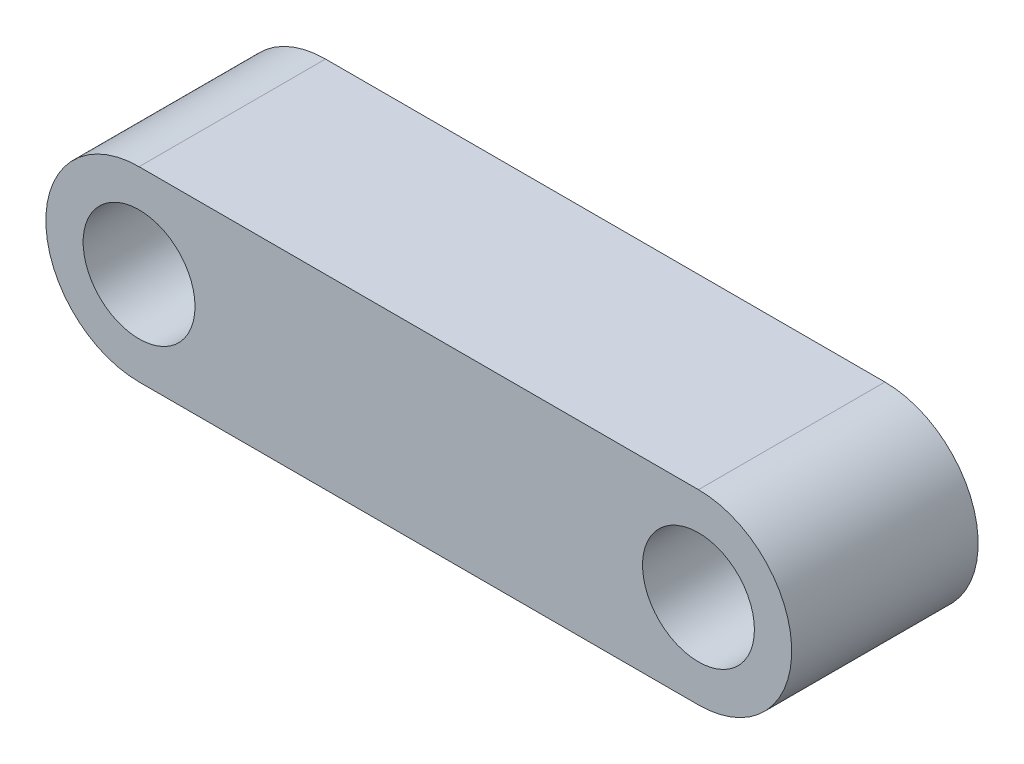
SolidWorks part; units mm, degrees
ref_plane "Front Plane" through (0, 0, 0) normal (0, 0, 1) x (1, 0, 0)
ref_plane "Top Plane" through (0, 0, 0) normal (0, 1, 0) x (1, 0, 0)
ref_plane "Right Plane" through (0, 0, 0) normal (1, 0, 0) x (0, 0, -1)
sketch "Sketch1" plane through (0, 0, 0) normal (0, 0, 1) x (1, 0, 0)
  line L1 (30, -10) -> (-30, -10)
  line L3 (30, 10) -> (-30, 10)
  line L5 (30, -10) -> (-30, 10) construction
  line L6 (30, 10) -> (-30, -10) construction
  arc A0 (-30, 10) -> (-30, -10) centre (-30, 0) ccw
  arc A1 (30, 10) -> (30, -10) centre (30, 0) cw
  point P0 (0, 0)
  point P7 (-40, 0)
  point P9 (40, 0)
  dimension "D3" = 80
  dimension "D1" = 60
  dimension "D2" = 20
extrude "Boss-Extrude1" add sketch "Sketch1" along normal blind 20
sketch "Sketch2" plane through (0, 0, 20) normal (0, 0, 1) x (1, 0, 0)
  circle A0 centre (-30, 0) radius 6
  circle A1 centre (30, 0) radius 6
  dimension "D1" = 12
extrude "Cut-Extrude1" cut sketch "Sketch2" against normal through all
